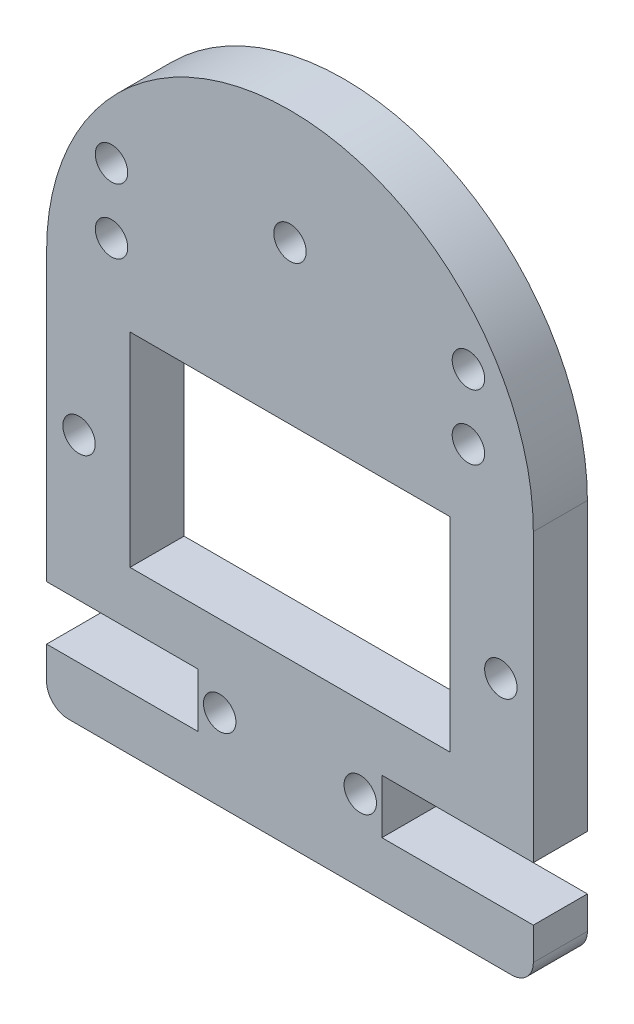
SolidWorks part; units mm, degrees
material "Acrílico (médio-alto impacto)"
ref_plane "Plano frontal" through (0, 0, 0) normal (0, 0, 1) x (1, 0, 0)
ref_plane "Plano superior" through (0, 0, 0) normal (0, 1, 0) x (1, 0, 0)
ref_plane "Plano direito" through (0, 0, 0) normal (1, 0, 0) x (0, 0, -1)
sketch "Esboço8" plane through (0, 0, 0) normal (0, 0, 1) x (1, 0, 0)
  line L0 (-24.2663, -3.25) -> (-24.2663, 13.25)
  line L2 (6.7337, -18.25) -> (20.7337, -18.25)
  line L3 (20.7337, -3.2223) -> (20.7337, 13.25)
  line L4 (-10.2663, -13.25) -> (-24.2663, -13.25)
  line L5 (-10.2663, -18.25) -> (-24.2663, -18.25)
  line L6 (20.7337, -3.25) -> (20.7337, -3.2223)
  line L7 (-24.2663, -18.25) -> (-24.2663, -21.25)
  line L8 (-10.2663, -13.25) -> (-10.2663, -18.25)
  line L9 (-24.2663, -13.25) -> (-24.2663, -3.25)
  line L10 (6.7337, -13.25) -> (20.7337, -13.25)
  line L11 (20.7337, -18.25) -> (20.7337, -21.25)
  line L12 (18.7337, -23.25) -> (-22.2663, -23.25)
  line L17 (6.7337, -13.25) -> (6.7337, -18.25)
  line L18 (20.7337, -13.25) -> (20.7337, -3.25)
  arc A0 (20.7337, 13.25) -> (-24.2663, 13.25) centre (-1.7663, 13.25) ccw
  arc A1 (-24.2663, -21.25) -> (-22.2663, -23.25) centre (-22.2663, -21.25) ccw
  arc A2 (18.7337, -23.25) -> (20.7337, -21.25) centre (18.7337, -21.25) ccw
  point P0 (0, 0)
  dimension "D1" = 2
extrude "Ressalto-extrusão2" add sketch "Esboço8" along normal blind 5
sketch "Esboço9" plane through (0, 0, 0) normal (0, 0, -1) x (-1, 0, 0)
  line L0 (-20.7337, -13.25) -> (-20.7337, 13.25) construction
  line L1 (16.5563, -8.25) -> (-13.0237, -8.25)
  line L2 (16.5563, -8.25) -> (16.5563, 10.6)
  line L3 (16.5563, 10.6) -> (-13.0237, 10.6)
  line L4 (-13.0237, -8.25) -> (-13.0237, 10.6)
  line L5 (24.2663, 13.25) -> (24.2663, -13.25) construction
  line L6 (-6.7337, -13.25) -> (-20.7337, -13.25) construction
  dimension "D1" = 7.71
  dimension "D2" = 7.71
  dimension "D3" = 5
extrude "Corte-extrusão1" cut sketch "Esboço9" against normal blind 5
sketch "Esboço10" plane through (0, 0, 0) normal (0, 0, -1) x (-1, 0, 0)
  line L0 (-6.7337, -13.25) -> (-20.7337, -13.25) construction
  line L1 (-20.7337, -13.25) -> (-20.7337, 13.25) construction
  line L2 (24.2663, 13.25) -> (24.2663, -13.25) construction
  line L3 (24.2663, -13.25) -> (10.2663, -13.25) construction
  circle A0 centre (-17.7337, 0) radius 1.5
  circle A1 centre (21.2663, 0) radius 1.5
  dimension "D1" = 13.25
  dimension "D2" = 3
  dimension "D3" = 3
  dimension "D4" = 13.25
extrude "Corte-extrusão2" cut sketch "Esboço10" against normal blind 5
sketch "Esboço12" plane through (0, 0, 5) normal (0, 0, 1) x (1, 0, 0)
  line L0 (6.7337, -18.25) -> (6.7337, -13.25) construction
  line L2 (-10.2663, -13.25) -> (-10.2663, -18.25) construction
  circle A0 centre (4.7337, -15.75) radius 1.5
  circle A1 centre (-8.2663, -15.75) radius 1.5
  point P10 (-10.2663, -15.75)
  dimension "D1" = 2
  dimension "D3" = 2
extrude "Corte-extrusão3" cut sketch "Esboço12" against normal blind 10
sketch "Esboço13" plane through (0, 0, 5) normal (0, 0, 1) x (1, 0, 0)
  line L1 (20.7337, -13.25) -> (20.7337, 13.25) construction
  arc A1 (20.7337, 13.25) -> (-24.2663, 13.25) centre (-1.7663, 13.25) ccw construction
  circle A2 centre (-1.7663, 25.15) radius 1.5
  point P5 (-1.7663, 35.75)
  dimension "D3" = 22.5
  dimension "D4" = 10.6
extrude "Corte-extrusão4" cut sketch "Esboço13" against normal blind 10
sketch "Esboço14" plane through (0, 0, 5) normal (0, 0, 1) x (1, 0, 0)
  line L0 (-24.2663, -13.25) -> (-10.2663, -13.25) construction
  line L2 (20.7337, -13.25) -> (20.7337, 13.25) construction
  line L3 (-16.5563, 10.6) -> (13.0237, 10.6) construction
  line L4 (-24.2663, 13.25) -> (-24.2663, -13.25) construction
  circle A0 centre (14.7337, 17.25) radius 1.5
  circle A1 centre (14.7337, 23.25) radius 1.5
  circle A2 centre (-18.2663, 23.25) radius 1.5
  circle A3 centre (-18.2663, 17.25) radius 1.5
  point P16 (-17.2663, -13.25)
  dimension "D1" = 6
  dimension "D2" = 6
  dimension "D3" = 6.65
  dimension "D4" = 6
  dimension "D5" = 6
  dimension "D6" = 6
  dimension "D7" = 30.5
extrude "Corte-extrusão5" cut sketch "Esboço14" against normal blind 76
